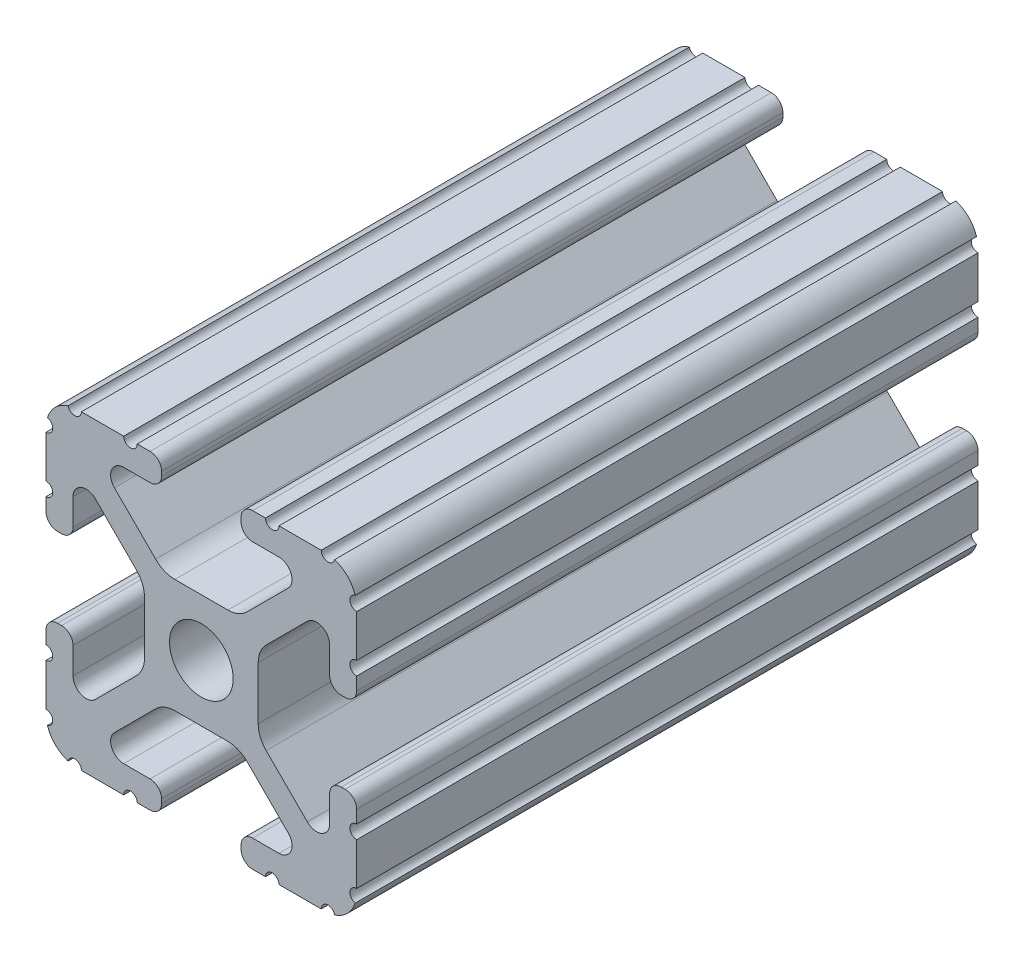
SolidWorks part; units mm, degrees
ref_plane "Front Plane" through (0, 0, 0) normal (0, 0, 1) x (1, 0, 0)
ref_plane "Top Plane" through (0, 0, 0) normal (0, 1, 0) x (1, 0, 0)
ref_plane "Right Plane" through (0, 0, 0) normal (1, 0, 0) x (0, 0, -1)
sketch "Sketch2" plane through (0, 0, 0) normal (0, 0, 1) x (1, 0, 0)
  line L0 (0, 12.7) -> (0, -12.7) construction
  line L1 (-12.7, 0) -> (12.7, 0) construction
  line L2 (3.2512, -12.7) -> (12.7, -12.7)
  line L3 (12.7, -12.7) -> (12.7, -3.2512)
  line L4 (3.2512, -12.7) -> (3.2512, -10.4902)
  line L5 (3.2512, -10.4902) -> (8.9276, -10.4902)
  line L6 (8.9276, -10.4902) -> (3.0856, -4.6482)
  line L7 (0, 0) -> (12.7, -12.7) construction
  line L8 (12.7, -3.2512) -> (10.4902, -3.2512)
  line L9 (10.4902, -3.2512) -> (10.4902, -8.9276)
  line L10 (10.4902, -8.9276) -> (4.6482, -3.0856)
  circle A0 centre (0, 0) radius 2.6035
  arc A1 (6.3485, -10.4902) -> (7.1039, -8.6665) centre (6.3485, -9.4219) ccw construction
  point P8 (0, -4.6482)
  dimension "Center Hole Diameter" = 5.207
  dimension "Rail Height" = 25.4
  dimension "Rail Width" = 25.4
  dimension "T-Slot Width" = 6.5024
  dimension "Slot Inner Width" = 14.8336
  dimension "Thickness" = 2.2098
  dimension "Slot Depth" = 5.842
  dimension "D1" = 2.2098
sketch "Sketch3" plane through (0, 0, 0) normal (1, 0, 0) x (0, 0, -1)
  line L0 (-25.4, -12.7) -> (25.4, -12.7) construction
  line L1 (-19.05, 0) -> (19.05, 0) construction
  dimension "Length" = 50.8
  dimension "D1" = 6.35
sketch "Sketch4" plane through (0, 0, 0) normal (0, 0, 1) x (1, 0, 0)
  line L0 (4.1904, -12.7) -> (10.1173, -12.7)
  line L1 (3.2512, -12.7) -> (12.7, -12.7) construction
  line L2 (3.2512, -12.7) -> (3.2512, -10.4902) construction
  line L3 (3.2512, -10.4902) -> (8.9276, -10.4902) construction
  line L4 (3.2512, -11.4294) -> (3.2512, -11.7608)
  line L5 (4.1904, -10.4902) -> (6.3485, -10.4902)
  line L6 (0, -4.6482) -> (2.164, -4.6482)
  line L7 (8.9276, -10.4902) -> (3.0856, -4.6482) construction
  line L8 (3.7373, -5.2999) -> (7.1039, -8.6665)
  line L9 (12.7, -12.7) -> (12.7, -3.2512) construction
  line L10 (10.4902, -8.9276) -> (4.6482, -3.0856) construction
  line L11 (10.4902, -3.2512) -> (10.4902, -8.9276) construction
  line L12 (10.4902, -6.3485) -> (10.4902, -4.1904)
  line L13 (12.7, -3.2512) -> (10.4902, -3.2512) construction
  line L14 (11.4294, -3.2512) -> (11.7608, -3.2512)
  line L15 (12.7, -4.1904) -> (12.7, -10.1173)
  line L16 (8.6665, -7.1039) -> (5.2999, -3.7373)
  line L17 (4.6482, 0) -> (4.6482, -2.164)
  line L18 (-12.7, 0) -> (12.7, 0) construction
  line L19 (0, -4.6482) -> (0, -2.6035)
  line L20 (0, 12.7) -> (0, -12.7) construction
  line L21 (4.6482, 0) -> (2.6035, 0)
  arc A0 (3.2512, -11.7608) -> (4.1904, -12.7) centre (4.1904, -11.7608) ccw
  arc A2 (3.2512, -11.4294) -> (4.1904, -10.4902) centre (4.1904, -11.4294) cw
  arc A3 (6.3485, -10.4902) -> (7.1039, -8.6665) centre (6.3485, -9.4219) ccw
  arc A4 (2.164, -4.6482) -> (3.7373, -5.2999) centre (2.164, -6.8732) cw
  arc A5 (10.1173, -12.7) -> (12.7, -10.1173) centre (10.1173, -10.1173) ccw
  arc A6 (8.6665, -7.1039) -> (10.4902, -6.3485) centre (9.4219, -6.3485) ccw
  arc A7 (10.4902, -4.1904) -> (11.4294, -3.2512) centre (11.4294, -4.1904) cw
  arc A8 (11.7608, -3.2512) -> (12.7, -4.1904) centre (11.7608, -4.1904) cw
  arc A9 (5.2999, -3.7373) -> (4.6482, -2.164) centre (6.8732, -2.164) cw
  circle A10 centre (0, 0) radius 2.6035 construction
  arc A11 (0, -2.6035) -> (2.6035, 0) centre (0, 0) ccw
  dimension "D1" = 2.5827
  dimension "D2" = 2.225
  dimension "D3" = 0.9392
extrude "Boss-Extrude1" add sketch "Sketch4" along normal mid plane 50.8
sketch "Sketch5" plane through (0, 0, 0) normal (0, 0, 1) x (1, 0, 0)
  line L0 (3.2512, -12.7) -> (12.7, -12.7) construction
  line L1 (4.1904, -10.4902) -> (6.3485, -10.4902) construction
  line L3 (0, 0) -> (12.7, -12.7) construction
  line L4 (6.3485, -10.4902) -> (6.3485, -12.7) construction
  line L5 (8.9276, -10.4902) -> (3.0856, -4.6482) construction
  circle A0 centre (10.3562, -12.7) radius 0.5524
  circle A1 centre (5.796, -12.7) radius 0.5524
  circle A2 centre (12.7, -10.3562) radius 0.5524
  circle A3 centre (12.7, -5.796) radius 0.5524
  point P10 (5.2694, -10.4902)
  point P12 (9.4219, -6.3485)
  dimension "D1" = 1.1049
extrude "Cut-Extrude1" cut sketch "Sketch5" against normal through all both and the other way through all
mirror "Mirror1" about plane through (0, 0, 0) normal (1, 0, 0) of bodies 137 134
mirror "Mirror2" about plane through (0, 0, 0) normal (0, 1, 0) of bodies 135
equation "\"D1@Boss-Extrude1\"=\"Length@Sketch3\""
equation "\"D1@Sketch2\"=\"Thickness@Sketch2\""
equation "\"D2@Sketch4\"=\"Slot Inner Width@Sketch2\"*0.15"
equation "\"D1@Sketch4\"=\"D3@Sketch4\"*2.75"
equation "\"D3@Sketch4\"=\"Thickness@Sketch2\"*0.425"
equation "\"D1@Sketch5\"=\"Thickness@Sketch2\"*0.5"
